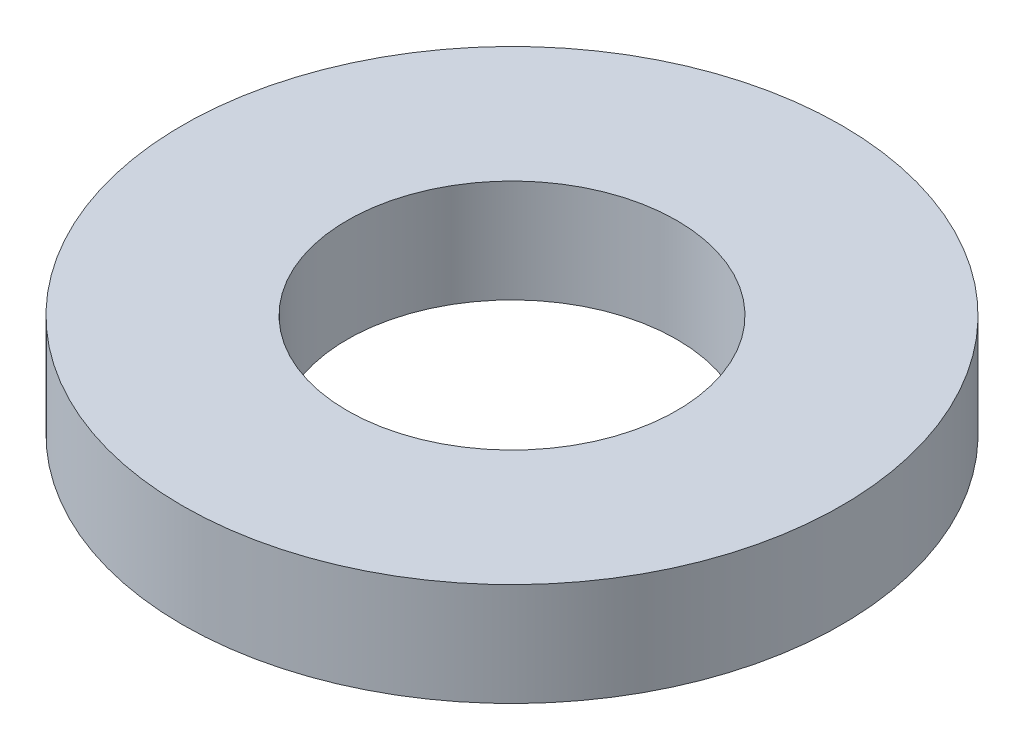
SolidWorks part; units mm, degrees
ref_plane "Front Plane" through (0, 0, 0) normal (0, 0, 1) x (1, 0, 0)
ref_plane "Top Plane" through (0, 0, 0) normal (0, 1, 0) x (1, 0, 0)
ref_plane "Right Plane" through (0, 0, 0) normal (1, 0, 0) x (0, 0, -1)
sketch "Sketch1" plane through (0, 0, 0) normal (0, 1, 0) x (1, 0, 0)
  circle A0 centre (0, 0) radius 8
  circle A1 centre (0, 0) radius 4
  dimension "D1" = 16
  dimension "D2" = 8
extrude "Boss-Extrude1" add sketch "Sketch1" along normal blind 2.5
